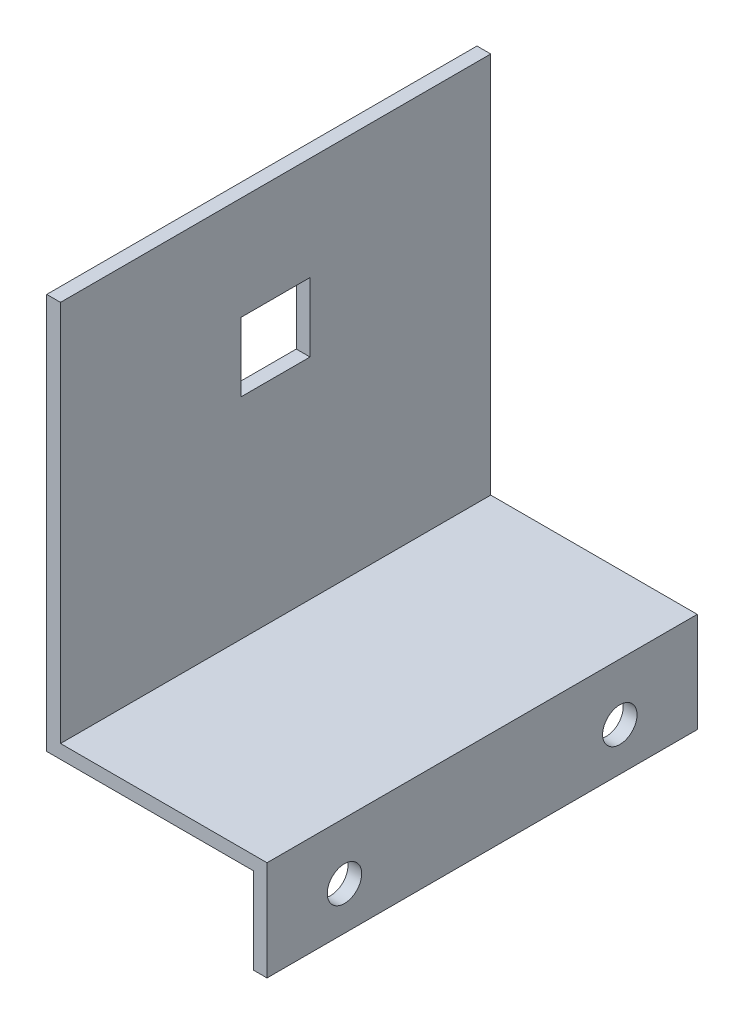
SolidWorks part; units mm, degrees
ref_plane "Front Plane" through (0, 0, 0) normal (0, 0, 1) x (1, 0, 0)
ref_plane "Top Plane" through (0, 0, 0) normal (0, 1, 0) x (1, 0, 0)
ref_plane "Right Plane" through (0, 0, 0) normal (1, 0, 0) x (0, 0, -1)
sketch "Sketch1" plane through (0, 0, 0) normal (0, 0, 1) x (1, 0, 0)
  line L0 (0, 0) -> (30.48, 0)
  line L1 (30.48, 0) -> (30.48, -12.7)
  line L2 (0, 0) -> (0, 58.42)
  line L3 (0, 58.42) -> (2.032, 58.42)
  line L4 (2.032, 58.42) -> (2.032, 2.032)
  line L5 (2.032, 2.032) -> (32.512, 2.032)
  line L6 (32.512, 2.032) -> (32.512, -12.7)
  line L7 (32.512, -12.7) -> (30.48, -12.7)
extrude "Boss-Extrude1" add sketch "Sketch1" against normal blind 63.5
ref_plane "Plane1" through (2.032, 0, 0) normal (1, 0, 0) x (0, 0, -1)
sketch "Sketch2" plane through (2.032, 0, 0) normal (1, 0, 0) x (0, 0, -1)
  line L0 (31.75, 58.42) -> (31.75, 38.1) construction
  line L3 (63.5, 58.42) -> (0, 58.42) construction
  line L5 (31.75, 43.18) -> (36.83, 43.18)
  line L6 (36.83, 43.18) -> (36.83, 33.02)
  line L7 (36.83, 33.02) -> (26.67, 33.02)
  line L8 (26.67, 33.02) -> (26.67, 43.18)
  line L9 (26.67, 43.18) -> (31.75, 43.18)
extrude "Cut-Extrude1" cut sketch "Sketch2" against normal through all
ref_plane "Plane3" through (30.48, 0, 0) normal (-1, 0, 0) x (0, 0, 1)
sketch "Sketch4" plane through (30.48, 0, 0) normal (-1, 0, 0) x (0, 0, 1)
  line L0 (-31.75, -6.35) -> (-52.07, -6.35) construction
  line L3 (-31.75, -12.7) -> (-31.75, 0) construction
  line L4 (-63.5, -12.7) -> (0, -12.7) construction
  line L5 (-63.5, 0) -> (0, 0) construction
  circle A0 centre (-52.07, -6.35) radius 2.54
  circle A1 centre (-11.43, -6.35) radius 2.54
extrude "Cut-Extrude2" cut sketch "Sketch4" against normal through all
